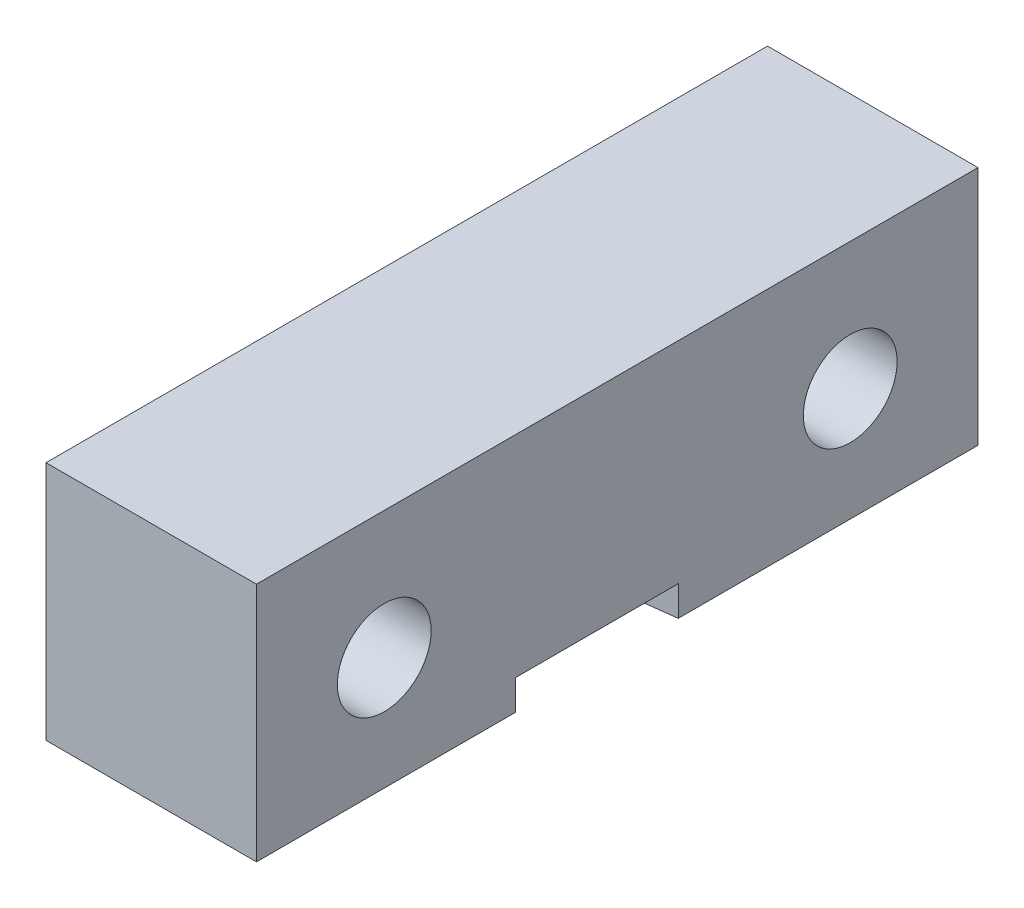
SolidWorks part; units mm, degrees
ref_plane "Front Plane" through (0, 0, 0) normal (0, 0, 1) x (1, 0, 0)
ref_plane "Top Plane" through (0, 0, 0) normal (0, 1, 0) x (1, 0, 0)
ref_plane "Right Plane" through (0, 0, 0) normal (1, 0, 0) x (0, 0, -1)
sketch "Sketch1" plane through (0, 0, 0) normal (0, 0, 1) x (1, 0, 0)
  line L1 (22.225, -25.4) -> (-22.225, -25.4)
  line L2 (22.225, -25.4) -> (22.225, 25.4)
  line L3 (22.225, 25.4) -> (-22.225, 25.4)
  line L4 (-22.225, -25.4) -> (-22.225, 25.4)
  line L5 (22.225, -25.4) -> (-22.225, 25.4) construction
  line L6 (22.225, 25.4) -> (-22.225, -25.4) construction
  point P0 (0, 0)
  dimension "D1" = 44.45
  dimension "D2" = 50.8
extrude "Boss-Extrude1" add sketch "Sketch1" along normal mid plane 152.4
sketch "Sketch2" plane through (22.225, 0, 0) normal (1, 0, 0) x (0, 0, -1)
  line L0 (-76.2, -25.4) -> (76.2, -25.4) construction
  circle A0 centre (-49.2125, -1.524) radius 6.731
  circle A1 centre (49.2125, -1.524) radius 6.731
  dimension "D4" = 13.462
  dimension "D1" = 98.425
  dimension "D2" = 49.2125
  dimension "D3" = 23.876
extrude "Cut-Extrude1" cut sketch "Sketch2" against normal up to next
sketch "Sketch3" plane through (22.225, 0, 0) normal (1, 0, 0) x (0, 0, -1)
  circle A0 centre (-49.2125, -1.524) radius 9.906
  circle A1 centre (49.2125, -1.524) radius 9.906
  dimension "D1" = 19.812
extrude "Cut-Extrude2" cut sketch "Sketch3" against normal blind 38.608
sketch "Sketch4" plane through (0, -25.4, 0) normal (0, -1, 0) x (1, 0, 0)
  line L4 (22.225, -12.8902) -> (22.225, 21.5318)
  line L5 (22.225, 76.2) -> (22.225, -76.2) construction
  line L6 (22.225, -12.8902) -> (0.9472, -10.2486)
  line L7 (22.225, 21.5318) -> (0.9472, 18.8901)
  circle A1 centre (2.756, 4.3208) radius 14.6812 construction
  arc A4 (0.9472, 18.8901) -> (0.9472, -10.2486) centre (2.756, 4.3208) ccw
extrude "Cut-Extrude3" cut sketch "Sketch4" against normal blind 6.35
sketch "Sketch5" plane through (0, -19.05, 0) normal (0, -1, 0) x (1, 0, 0)
  circle A0 centre (2.756, 4.3208) radius 12.0142
extrude "Cut-Extrude4" cut sketch "Sketch5" against normal blind 3.81
sketch "Sketch6" plane through (0, -19.05, 0) normal (0, -1, 0) x (1, 0, 0)
  circle A0 centre (2.756, 4.3208) radius 14.6812
extrude "Cut-Extrude5" cut sketch "Sketch6" against normal blind 1.5875
